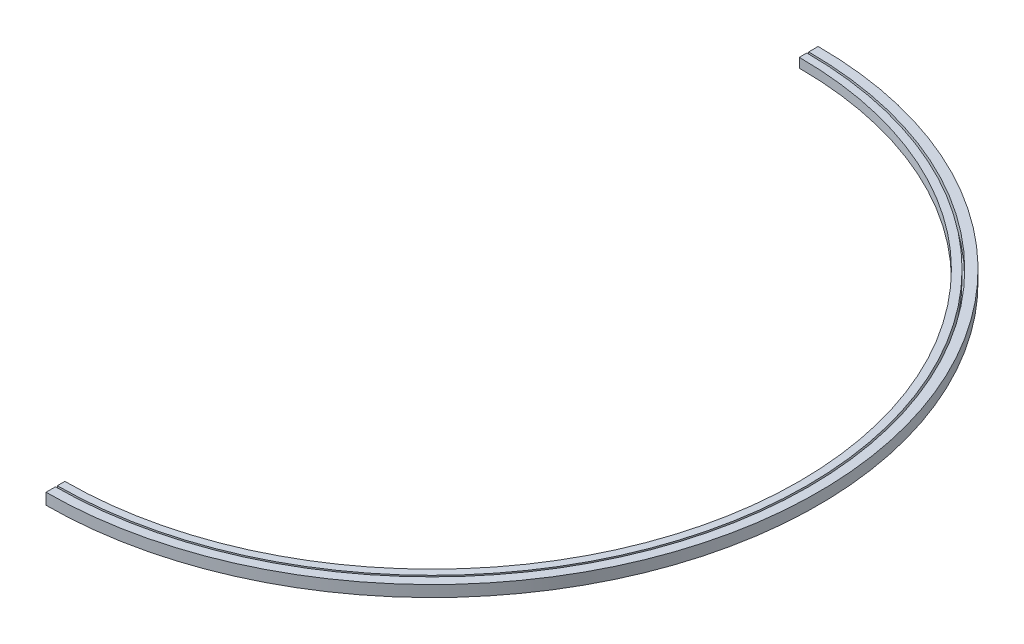
SolidWorks part; units mm, degrees
ref_plane "Front Plane" through (0, 0, 0) normal (0, 0, 1) x (1, 0, 0)
ref_plane "Top Plane" through (0, 0, 0) normal (0, 1, 0) x (1, 0, 0)
ref_plane "Right Plane" through (0, 0, 0) normal (1, 0, 0) x (0, 0, -1)
sketch "Sketch1" plane through (0, 0, 0) normal (0, 1, 0) x (1, 0, 0)
  line L0 (0, 4100) -> (0, -4100)
  circle A0 centre (0, 0) radius 4000
  circle A1 centre (0, 0) radius 3980
  circle A2 centre (0, 0) radius 3900
  circle A3 centre (0, 0) radius 4100
  dimension "D1" = 8000
  dimension "D2" = 7960
  dimension "D3" = 7800
  dimension "D4" = 8200
extrude "Boss-Extrude1" add sketch "Sketch1" along normal blind 100 contours L0 A3 A0 | A2 L0 A1
sketch "Sketch2" plane through (0, 0, 0) normal (0, -1, 0) x (1, 0, 0)
  line L0 (0, 4100) -> (0, -4100)
  circle A0 centre (0, 0) radius 4100
  circle A1 centre (0, 0) radius 3900
  arc M3 (0, -3980) -> (0, 3980) centre (0, 0) ccw
extrude "Boss-Extrude2" add sketch "Sketch2" along normal blind 20 contours L0 A0 M3
